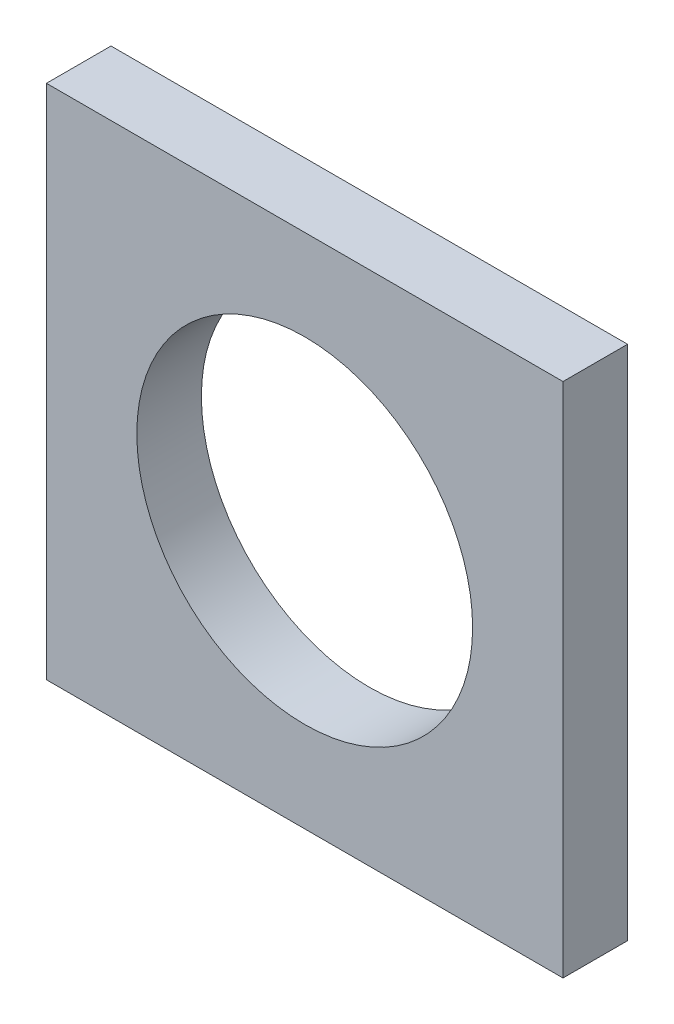
SolidWorks part; units mm, degrees
ref_plane "Front Plane" through (0, 0, 0) normal (0, 0, 1) x (1, 0, 0)
ref_plane "Top Plane" through (0, 0, 0) normal (0, 1, 0) x (1, 0, 0)
ref_plane "Right Plane" through (0, 0, 0) normal (1, 0, 0) x (0, 0, -1)
sketch "Sketch1" plane through (0, 0, 0) normal (0, 0, 1) x (1, 0, 0)
  line L1 (-10, -10) -> (10, -10)
  line L2 (-10, -10) -> (-10, 10)
  line L3 (-10, 10) -> (10, 10)
  line L4 (10, -10) -> (10, 10)
  line L5 (-10, -10) -> (10, 10) construction
  line L6 (-10, 10) -> (10, -10) construction
  circle A0 centre (0, 0) radius 6.5
  point P0 (0, 0)
  dimension "D3" = 13
  dimension "D1" = 20
  dimension "D2" = 20
extrude "Boss-Extrude1" add sketch "Sketch1" along normal blind 2.5
equation "\"D2@Sketch1\"=\"D1@Sketch1\""
